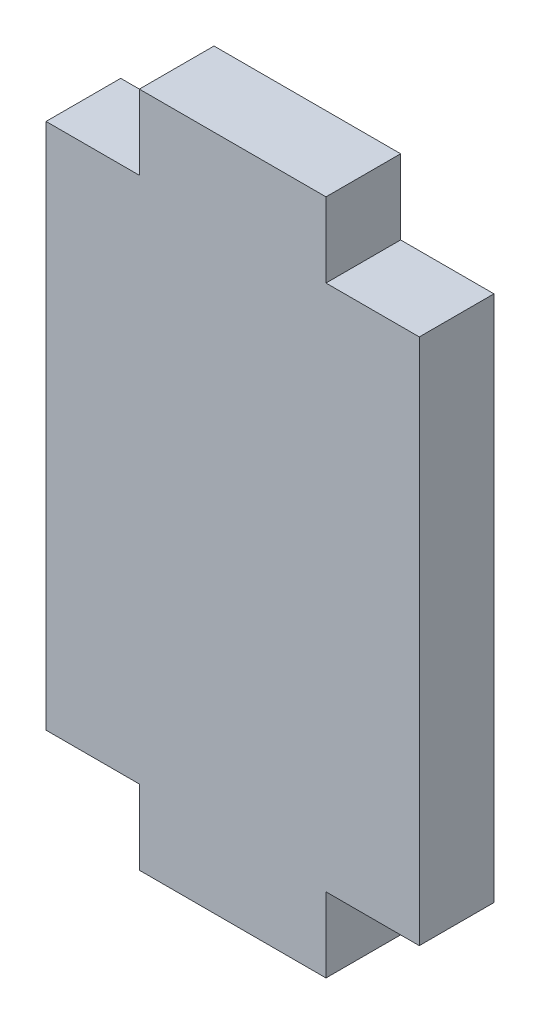
SolidWorks part; units mm, degrees
ref_plane "Front Plane" through (0, 0, 0) normal (0, 0, 1) x (1, 0, 0)
ref_plane "Top Plane" through (0, 0, 0) normal (0, 1, 0) x (1, 0, 0)
ref_plane "Right Plane" through (0, 0, 0) normal (1, 0, 0) x (0, 0, -1)
sketch "Sketch1" plane through (0, 0, 0) normal (0, 0, 1) x (1, 0, 0)
  line L0 (-10, 14.125) -> (-10, -14.125)
  line L5 (-10, 14.125) -> (10, -14.125) construction
  line L6 (-10, -14.125) -> (10, 14.125) construction
  line L7 (-10, -14.125) -> (-5, -14.125)
  line L8 (-5, -14.125) -> (-5, -18.125)
  line L9 (-5, -18.125) -> (5, -18.125)
  line L10 (5, -18.125) -> (5, -14.125)
  line L11 (5, -14.125) -> (10, -14.125)
  line L12 (10, -14.125) -> (10, 14.125)
  line L13 (10, 14.125) -> (5, 14.125)
  line L14 (5, 14.125) -> (5, 18.125)
  line L15 (5, 18.125) -> (-5, 18.125)
  line L16 (-5, 18.125) -> (-5, 14.125)
  line L17 (-5, 14.125) -> (-10, 14.125)
  line L18 (0, 0) -> (0, -29.4192) construction
  point P0 (0, 0)
  point P12 (-12.8042, 20.0447)
  point P15 (-12.4994, -18.2155)
  point P18 (-13.1091, -18.5966)
  point P19 (-5, 31.335)
  point P20 (-5, 23.8597)
  point P21 (0, 0)
  point P22 (0, 0)
  dimension "D1" = 10
  dimension "D2" = 5
  dimension "D3" = 4
  dimension "D4" = 28.25
extrude "Boss-Extrude1" add sketch "Sketch1" along normal blind 4
